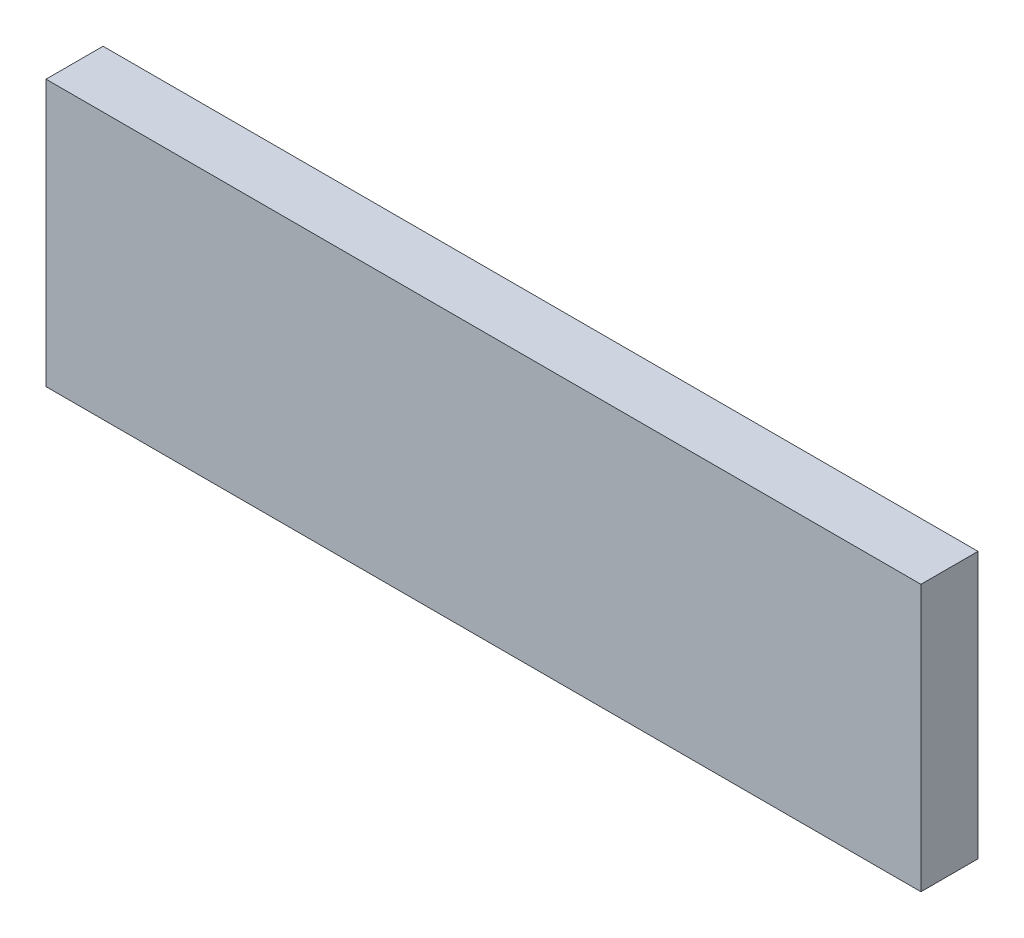
SolidWorks part; units mm, degrees
material "PTFE (general)"
ref_plane "Front Plane" through (0, 0, 0) normal (0, 0, 1) x (1, 0, 0)
ref_plane "Top Plane" through (0, 0, 0) normal (0, 1, 0) x (1, 0, 0)
ref_plane "Right Plane" through (0, 0, 0) normal (1, 0, 0) x (0, 0, -1)
sketch "Sketch1" plane through (0, 0, 0) normal (0, 0, 1) x (1, 0, 0)
  line L1 (0, 0) -> (46, 0)
  line L2 (0, 0) -> (0, 14)
  line L3 (0, 14) -> (46, 14)
  line L4 (46, 0) -> (46, 14)
  dimension "D1" = 46
  dimension "D2" = 14
extrude "Boss-Extrude1" add sketch "Sketch1" along normal blind 3
